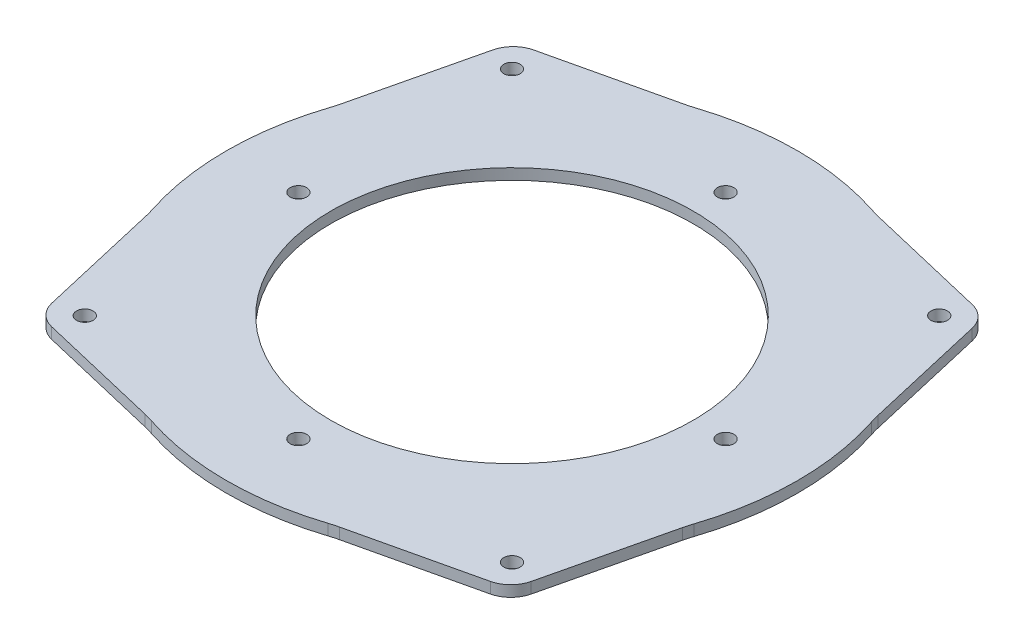
SolidWorks part; units mm, degrees
material "6061-T6 (SS)"
ref_plane "Front Plane" through (0, 0, 0) normal (0, 0, 1) x (1, 0, 0)
ref_plane "Top Plane" through (0, 0, 0) normal (0, 1, 0) x (1, 0, 0)
ref_plane "Right Plane" through (0, 0, 0) normal (1, 0, 0) x (0, 0, -1)
sketch "Sketch2" plane through (0, 0, 0) normal (0, 1, 0) x (1, 0, 0)
  line L0 (49.872, -261.8935) -> (473.872, -261.8935) construction
  line L1 (17.8971, 48.9297) -> (40.1493, 43.6512)
  line L2 (43.8664, 39.9141) -> (49.0252, 17.6338)
  line L3 (48.9297, -17.8971) -> (43.6512, -40.1493)
  line L4 (39.9141, -43.8664) -> (17.6338, -49.0252)
  line L5 (-17.8971, -48.9297) -> (-40.1493, -43.6512)
  line L6 (-43.8664, -39.9141) -> (-49.0252, -17.6338)
  line L7 (-48.9297, 17.8971) -> (-43.6512, 40.1493)
  line L8 (-39.9141, 43.8664) -> (-17.6338, 49.0252)
  line L9 (0.1397, 51.9998) -> (-0.1397, -51.9998) construction
  line L10 (-51.9998, 0.1397) -> (51.9998, -0.1397) construction
  line L11 (0, 38.8907) -> (0, -38.8907) construction
  line L12 (-38.8907, 38.8907) -> (38.8907, 38.8907) construction
  line L13 (-38.8907, 38.8907) -> (-38.8907, -38.8907) construction
  line L14 (-38.8907, -38.8907) -> (38.8907, -38.8907) construction
  line L15 (38.8907, 38.8907) -> (38.8907, -38.8907) construction
  line L16 (-38.8907, 0) -> (38.8907, 0) construction
  line L17 (0, 0) -> (0, 38.8907) construction
  line L18 (0, 0) -> (38.8907, 0) construction
  circle A0 centre (0, 0) radius 30 construction
  arc A3 (-17.6338, 49.0252) -> (-15.9939, 49.4792) centre (-22.1454, 68.5097) ccw
  arc A4 (0.1397, 51.9998) -> (-15.9939, 49.4792) centre (0, 0) ccw
  arc A5 (16.2596, 49.3926) -> (0.1397, 51.9998) centre (0, 0) ccw
  arc A6 (16.2596, 49.3926) -> (17.8971, 48.9297) centre (22.5132, 68.3897) ccw
  arc A7 (43.8664, 39.9141) -> (40.1493, 43.6512) centre (38.9952, 38.7862) ccw
  arc A8 (49.0252, 17.6338) -> (49.4792, 15.9939) centre (68.5097, 22.1454) ccw
  arc A9 (49.3926, -16.2596) -> (49.4792, 15.9939) centre (0, 0) ccw
  arc A10 (49.3926, -16.2596) -> (48.9297, -17.8971) centre (68.3897, -22.5132) ccw
  arc A11 (39.9141, -43.8664) -> (43.6512, -40.1493) centre (38.7862, -38.9952) ccw
  arc A12 (17.6338, -49.0252) -> (15.9939, -49.4792) centre (22.1454, -68.5097) ccw
  arc A13 (-16.2596, -49.3926) -> (15.9939, -49.4792) centre (0, 0) ccw
  arc A14 (-16.2596, -49.3926) -> (-17.8971, -48.9297) centre (-22.5132, -68.3897) ccw
  arc A15 (-43.8664, -39.9141) -> (-40.1493, -43.6512) centre (-38.9952, -38.7862) ccw
  arc A16 (-49.0252, -17.6338) -> (-49.4792, -15.9939) centre (-68.5097, -22.1454) ccw
  arc A17 (-49.3926, 16.2596) -> (-49.4792, -15.9939) centre (0, 0) ccw
  arc A18 (-49.3926, 16.2596) -> (-48.9297, 17.8971) centre (-68.3897, 22.5132) ccw
  arc A19 (-39.9141, 43.8664) -> (-43.6512, 40.1493) centre (-38.7862, 38.9952) ccw
  circle A20 centre (-38.8907, 38.8907) radius 1.5
  circle A21 centre (38.8907, 38.8907) radius 1.5
  circle A22 centre (38.8907, -38.8907) radius 1.5
  circle A23 centre (-38.8907, -38.8907) radius 1.5
  circle A27 centre (0, 0) radius 33
  circle A28 centre (0, 38.8907) radius 1.5
  circle A29 centre (38.8907, 0) radius 1.5
  circle A30 centre (0, -38.8907) radius 1.5
  circle A31 centre (-38.8907, 0) radius 1.5
  point P23 (0, 0)
  point P66 (0, 0)
  point P71 (0, 0)
  dimension "D1" = 60
  dimension "D2" = 3
  dimension "D3" = 66
  dimension "D5" = 90
  dimension "D6" = 38.8907
  dimension "D4" = 4
extrude "Boss-Extrude1" add sketch "Sketch2" along normal blind 2
